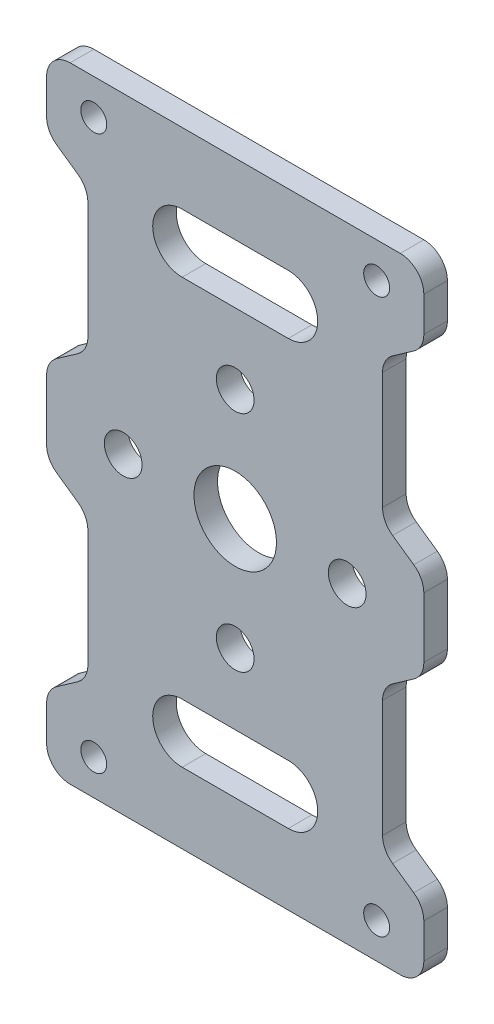
SolidWorks part; units mm, degrees
material "cf"
ref_plane "Front Plane" through (0, 0, 0) normal (0, 0, 1) x (1, 0, 0)
ref_plane "Top Plane" through (0, 0, 0) normal (0, 1, 0) x (1, 0, 0)
ref_plane "Right Plane" through (0, 0, 0) normal (1, 0, 0) x (0, 0, -1)
sketch "Sketch1" plane through (0, 0, 0) normal (0, 0, 1) x (1, 0, 0)
  line L0 (0, 0) -> (0, 50000) construction
  line L1 (-16, -26.5) -> (16, -26.5)
  line L2 (-16, -26.5) -> (-16, 26.5)
  line L3 (-16, 26.5) -> (16, 26.5)
  line L4 (16, -26.5) -> (16, 26.5)
  line L5 (-12, 23.5) -> (12, 23.5) construction
  line L6 (-12, 23.5) -> (-12, -23.5) construction
  line L7 (-14.5958, 21) -> (14.5958, 21) construction
  line L8 (-14.5958, 21) -> (-14.5958, 26) construction
  line L9 (-14.5958, 26) -> (14.5958, 26) construction
  line L10 (14.5958, 21) -> (14.5958, 26) construction
  line L11 (-14.5958, 21) -> (14.5958, 26) construction
  line L12 (-14.5958, 26) -> (14.5958, 21) construction
  circle A0 centre (0, 0) radius 9.5 construction
  circle A1 centre (0, 9.5) radius 1.6
  circle A2 centre (9.5, 0) radius 1.6
  circle A3 centre (0, -9.5) radius 1.6
  circle A4 centre (-9.5, 0) radius 1.6
  circle A5 centre (-12, 23.5) radius 1.1
  circle A6 centre (12, -23.5) radius 1.1
  circle A7 centre (12, 23.5) radius 1.1
  circle A8 centre (-12, -23.5) radius 1.1
  circle A9 centre (0, 0) radius 3.5
  circle A10 centre (0, 0) radius 18.75 construction
  point P0 (0, 0)
  point P19 (0, 0)
  point P25 (0, 23.5)
  point P30 (0, 23.5)
  point P33 (-12, 0)
  point P36 (16, 0)
  dimension "D1" = 19
  dimension "D2" = 3.2
  dimension "D4" = 2.2
  dimension "D8" = 7
  dimension "D10" = 37.5
  dimension "D5" = 24
  dimension "D6" = 47
  dimension "D7" = 53
  dimension "D9" = 5
  dimension "D11" = 32
  dimension "D3" = 4
extrude "Boss-Extrude1" add sketch "Sketch1" along normal blind 2
sketch "Sketch2" plane through (0, 0, 2) normal (0, 0, 1) x (1, 0, 0)
  line L0 (-16, 20.5) -> (-12.5, 18.0493)
  line L3 (-12.5, 18.0493) -> (-12.5, 6.0493)
  line L4 (-12.5, 6.0493) -> (-16, 3.5985)
  line L5 (0, 0) -> (-50000, 0) construction
  line L14 (0, 0) -> (0, 50000) construction
  line L15 (12.5, 6.0493) -> (16, 3.5985)
  line L16 (12.5, 18.0493) -> (12.5, 6.0493)
  line L17 (16, 20.5) -> (12.5, 18.0493)
  line L18 (16, -20.5) -> (12.5, -18.0493)
  line L19 (12.5, -18.0493) -> (12.5, -6.0493)
  line L20 (12.5, -6.0493) -> (16, -3.5985)
  line L21 (-12.5, -6.0493) -> (-16, -3.5985)
  line L22 (-12.5, -18.0493) -> (-12.5, -6.0493)
  line L23 (-16, -20.5) -> (-12.5, -18.0493)
  line L28 (-4.5, 18) -> (4.5, 18) construction
  line L29 (-4.5, 20.5) -> (4.5, 20.5)
  line L30 (-4.5, 15.5) -> (4.5, 15.5)
  line L31 (-4.5, -18) -> (4.5, -18) construction
  line L32 (-4.5, -20.5) -> (4.5, -20.5)
  line L33 (-4.5, -15.5) -> (4.5, -15.5)
  line L34 (-16, 20.5) -> (-16, 3.5985)
  line L35 (-16, -3.5985) -> (-16, -20.5)
  line L36 (16, -20.5) -> (16, -3.5985)
  line L37 (16, 3.5985) -> (16, 20.5)
  circle A2 centre (-12, 23.5) radius 1.1 construction
  arc A4 (-4.5, 20.5) -> (-4.5, 15.5) centre (-4.5, 18) ccw
  arc A5 (4.5, 15.5) -> (4.5, 20.5) centre (4.5, 18) ccw
  arc A7 (-4.5, -20.5) -> (-4.5, -15.5) centre (-4.5, -18) cw
  arc A8 (4.5, -15.5) -> (4.5, -20.5) centre (4.5, -18) cw
  point P30 (0, 18)
  point P37 (0, -18)
  dimension "D2" = 3
  dimension "D9" = 2.5
  dimension "D5" = 12
  dimension "D6" = 3.5
  dimension "D7" = 9
extrude "Cut-Extrude1" cut sketch "Sketch2" against normal through all both and the other way through all
fillet "Fillet1" radius 2 20 edges at (16, 3.5985, 1) (16, -3.5985, 1) (12.5, -6.0493, 1) (12.5, -18.0493, 1) (16, -20.5, 1) (16, -26.5, 1) (-16, -20.5, 1) (-12.5, -18.0493, 1) (-12.5, -6.0493, 1) (-16, -3.5985, 1) (-16, 3.5985, 1) (-12.5, 6.0493, 1) (-12.5, 18.0493, 1) (-16, 20.5, 1) (-16, 26.5, 1) (16, 26.5, 1) (16, 20.5, 1) (12.5, 18.0493, 1) (12.5, 6.0493, 1) (-16, -26.5, 1)
